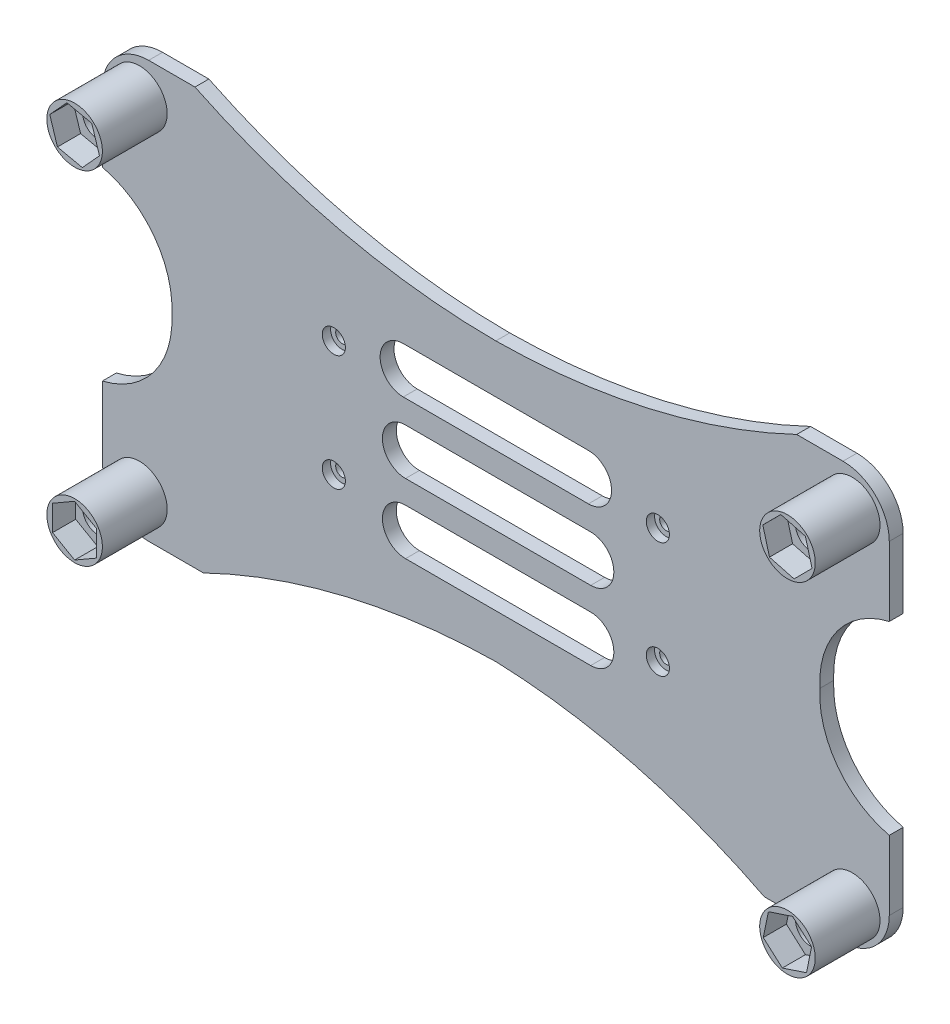
SolidWorks part; units mm, degrees
ref_plane "前视基准面" through (0, 0, 0) normal (0, 0, 1) x (1, 0, 0)
ref_plane "上视基准面" through (0, 0, 0) normal (0, 1, 0) x (1, 0, 0)
ref_plane "右视基准面" through (0, 0, 0) normal (1, 0, 0) x (0, 0, -1)
sketch "草图1" plane through (0, 0, 0) normal (0, 0, 1) x (1, 0, 0)
  line L1 (-72.5741, 45.4874) -> (77.4259, 45.4874)
  line L2 (-82.5741, 35.4874) -> (-82.5741, -34.5126)
  line L3 (-72.5741, -44.5126) -> (77.4259, -44.5126)
  line L4 (87.4259, 35.4874) -> (87.4259, -34.5126)
  arc A0 (-72.5741, 45.4874) -> (-82.5741, 35.4874) centre (-72.5741, 35.4874) ccw
  arc A1 (-72.5741, -44.5126) -> (-82.5741, -34.5126) centre (-72.5741, -34.5126) cw
  arc A2 (87.4259, 35.4874) -> (77.4259, 45.4874) centre (77.4259, 35.4874) ccw
  arc A3 (87.4259, -34.5126) -> (77.4259, -44.5126) centre (77.4259, -34.5126) cw
  dimension "D1" = 10
  dimension "D2" = 10
  dimension "D3" = 10
  dimension "D4" = 10
  dimension "D5" = 90
  dimension "D6" = 170
extrude "凸台-拉伸1" add sketch "草图1" along normal blind 3
ref_plane "for screw hole" through (0, 0, 3) normal (0, 0, 1) x (1, 0, 0)
sketch "草图2" plane through (0, 0, 3) normal (0, 0, 1) x (1, 0, 0)
  line L0 (77.4259, 45.4874) -> (-72.5741, 45.4874) construction
  line L1 (-82.5741, 35.4874) -> (-82.5741, -34.5126) construction
  line L2 (-72.5741, -44.5126) -> (77.4259, -44.5126) construction
  line L3 (87.4259, -34.5126) -> (87.4259, 35.4874) construction
  line L4 (-60.7497, -44.5126) -> (60.4378, -44.5126)
  line L5 (-62.5741, 45.4874) -> (67.4259, 45.4874)
  line L6 (87.4259, 20.4874) -> (87.4259, -19.5126)
  line L7 (-82.5741, 20.4874) -> (-82.5741, -19.5126)
  line L8 (-17.5741, 15) -> (22.4259, 15) construction
  line L9 (-17.5741, 20) -> (22.4259, 20)
  line L10 (-17.5741, 10) -> (22.4259, 10)
  line L11 (-17.0794, 0) -> (22.9206, 0) construction
  line L12 (-17.0794, 5) -> (22.9206, 5)
  line L13 (-17.0794, -5) -> (22.9206, -5)
  line L14 (-17.0794, -15) -> (22.9206, -15) construction
  line L15 (-17.0794, -10) -> (22.9206, -10)
  line L16 (-17.0794, -20) -> (22.9206, -20)
  circle A0 centre (-32.5741, 12.9874) radius 1.4
  circle A1 centre (-32.5741, -12.0126) radius 1.4
  circle A2 centre (37.4259, 12.9874) radius 1.4
  circle A3 centre (37.4259, -12.0126) radius 1.4
  arc A4 (67.4259, 45.4874) -> (2.4259, 30.4874) centre (1.0956, 184.5854) cw
  arc A5 (-62.5741, 45.4874) -> (2.4259, 30.4874) centre (2.8104, 180.4869) ccw
  arc A6 (-60.7497, -44.5126) -> (2.4259, -29.5126) centre (4.6684, -179.4958) cw
  arc A7 (60.4378, -44.5126) -> (2.4259, -29.5126) centre (-2.3985, -167.85) ccw
  arc A8 (87.4259, 20.4874) -> (72.4259, 0.4874) centre (91.8434, 1.5492) ccw
  arc A9 (87.4259, -19.5126) -> (72.4259, 0.4874) centre (91.8434, -0.5745) cw
  arc A10 (-82.5741, 20.4874) -> (-67.5741, 0.4874) centre (-86.9917, 1.5492) cw
  arc A11 (-82.5741, -19.5126) -> (-67.5741, 0.4874) centre (-86.9917, -0.5745) ccw
  arc A12 (-17.5741, 20) -> (-17.5741, 10) centre (-17.5741, 15) ccw
  arc A13 (22.4259, 10) -> (22.4259, 20) centre (22.4259, 15) ccw
  arc A14 (-17.0794, 5) -> (-17.0794, -5) centre (-17.0794, 0) ccw
  arc A15 (22.9206, -5) -> (22.9206, 5) centre (22.9206, 0) ccw
  arc A16 (-17.0794, -10) -> (-17.0794, -20) centre (-17.0794, -15) ccw
  arc A17 (22.9206, -20) -> (22.9206, -10) centre (22.9206, -15) ccw
  point P12 (2.4259, 30.4874)
  point P13 (2.4259, -29.5126)
  point P16 (-62.5741, 45.4874)
  point P17 (67.4259, 45.4874)
  point P18 (-60.7497, -44.5126)
  point P19 (60.4378, -44.5126)
  point P29 (-67.5741, 0.4874)
  point P33 (72.4259, 0.4874)
  point P34 (-82.5741, 20.4874)
  point P35 (-82.5741, -19.5126)
  point P36 (87.4259, -19.5126)
  point P37 (87.4259, 20.4874)
  point P54 (2.4259, 15)
  point P61 (2.9206, 0)
  point P68 (2.9206, -15)
  dimension "D2" = 2.8
  dimension "D3" = 2.8
  dimension "D4" = 2.8
  dimension "D8" = 32.5
  dimension "D9" = 50
  dimension "D10" = 50
  dimension "D11" = 2.8
  dimension "D21" = 45
  dimension "D29" = 15
  dimension "D5" = 70
  dimension "D6" = 70
  dimension "D7" = 25
  dimension "D12" = 25
  dimension "D13" = 32.5
  dimension "D14" = 85
  dimension "D15" = 15
  dimension "D16" = 85
  dimension "D17" = 15
  dimension "D18" = 20
  dimension "D19" = 20
  dimension "D20" = 26.9881
  dimension "D22" = 15
  dimension "D23" = 15
  dimension "D24" = 45
  dimension "D25" = 25
  dimension "D26" = 25
  dimension "D27" = 25
  dimension "D28" = 25
  dimension "D30" = 15
  dimension "D31" = 15
extrude "切除-拉伸1" cut sketch "草图2" against normal blind 10 and the other way blind 42
ref_plane "for outer screw hole" through (0, 0, 3) normal (0, 0, 1) x (1, 0, 0)
sketch "草图3" plane through (0, 0, 3) normal (0, 0, 1) x (1, 0, 0)
  circle A0 centre (-32.5741, 12.9874) radius 2.5
  circle A1 centre (37.4259, 12.9874) radius 2.5
  circle A2 centre (37.4259, -12.0126) radius 2.5
  circle A3 centre (-32.5741, -12.0126) radius 2.5
  dimension "D1" = 5
  dimension "D2" = 5
  dimension "D3" = 5
  dimension "D4" = 5
extrude "切除-拉伸2" cut sketch "草图3" against normal blind 1.8
ref_plane "for stands" through (0, 0, 3) normal (0, 0, 1) x (1, 0, 0)
sketch "草图7" plane through (0, 0, 3) normal (0, 0, 1) x (1, 0, 0)
  line L0 (77.4259, 45.4874) -> (67.4259, 45.4874) construction
  line L1 (-82.5741, 35.4874) -> (-82.5741, 20.4874) construction
  line L2 (-72.5741, -44.5126) -> (-60.7497, -44.5126) construction
  line L3 (87.4259, -34.5126) -> (87.4259, -19.5126) construction
  circle A0 centre (-74.5741, 37.4874) radius 6
  circle A1 centre (-74.5741, -36.5126) radius 6
  circle A2 centre (79.4259, 37.4874) radius 6
  circle A3 centre (79.4259, -36.5126) radius 6
  point P12 (79.4259, -30.5126)
  point P14 (79.4259, 31.4874)
  dimension "D1" = 12
  dimension "D2" = 12
  dimension "D3" = 12
  dimension "D4" = 12
  dimension "D7" = 8
  dimension "D5" = 8
  dimension "D6" = 8
  dimension "D8" = 8
  dimension "D9" = 8
  dimension "D10" = 8
  dimension "D11" = 8
  dimension "D12" = 8
extrude "凸台-拉伸4" add sketch "草图7" along normal blind 14
ref_plane "button left hole" through (0, 0, 17) normal (0, 0, 1) x (1, 0, 0)
ref_plane "up left hole" through (0, 0, 17) normal (0, 0, 1) x (1, 0, 0)
ref_plane "up right hole" through (0, 0, 17) normal (0, 0, 1) x (1, 0, 0)
ref_plane "button right hole" through (0, 0, 17) normal (0, 0, 1) x (1, 0, 0)
sketch "草图9" plane through (0, 0, 17) normal (0, 0, 1) x (1, 0, 0)
  line L1 (-69.811, -39.2626) -> (-69.811, -33.7626)
  line L2 (-69.811, -33.7626) -> (-74.5741, -31.0126)
  line L3 (-74.5741, -31.0126) -> (-79.3373, -33.7626)
  line L4 (-79.3373, -33.7626) -> (-79.3373, -39.2626)
  line L5 (-79.3373, -39.2626) -> (-74.5741, -42.0126)
  line L6 (-74.5741, -42.0126) -> (-69.811, -39.2626)
  circle A0 centre (-74.5741, -36.5126) radius 4.7631 construction
  circle A1 centre (-74.5741, -36.5126) radius 6 construction
  dimension "D1" = 5.5
  dimension "D2" = 0
extrude "button left nut " cut sketch "草图9" against normal blind 5
sketch "草图10" plane through (0, 0, 17) normal (0, 0, 1) x (1, 0, 0)
  line L1 (-72.9093, 32.2454) -> (-69.202, 36.3081)
  line L2 (-69.202, 36.3081) -> (-70.8668, 41.5501)
  line L3 (-70.8668, 41.5501) -> (-76.2389, 42.7294)
  line L4 (-76.2389, 42.7294) -> (-79.9462, 38.6666)
  line L5 (-79.9462, 38.6666) -> (-78.2814, 33.4246)
  line L6 (-78.2814, 33.4246) -> (-72.9093, 32.2454)
  circle A0 centre (-74.5741, 37.4874) radius 4.7631 construction
  circle A1 centre (-74.5741, 37.4874) radius 6 construction
  dimension "D1" = 5.5
  dimension "D2" = 0
extrude "up left nut" cut sketch "草图10" against normal blind 5
sketch "草图11" plane through (0, 0, 17) normal (0, 0, 1) x (1, 0, 0)
  line L1 (80.8593, 32.1775) -> (84.7411, 36.0738)
  line L2 (84.7411, 36.0738) -> (83.3077, 41.3838)
  line L3 (83.3077, 41.3838) -> (77.9924, 42.7973)
  line L4 (77.9924, 42.7973) -> (74.1106, 38.9009)
  line L5 (74.1106, 38.9009) -> (75.5441, 33.591)
  line L6 (75.5441, 33.591) -> (80.8593, 32.1775)
  circle A0 centre (79.4259, 37.4874) radius 4.7631 construction
  circle A2 centre (79.4259, 37.4874) radius 6 construction
  dimension "D2" = 0
  dimension "D1" = 5.5
extrude "up right nut" cut sketch "草图11" against normal blind 5
sketch "草图12" plane through (0, 0, 17) normal (0, 0, 1) x (1, 0, 0)
  line L1 (83.5366, -40.1666) -> (84.6457, -34.7796)
  line L2 (84.6457, -34.7796) -> (80.535, -31.1256)
  line L3 (80.535, -31.1256) -> (75.3151, -32.8586)
  line L4 (75.3151, -32.8586) -> (74.2061, -38.2456)
  line L5 (74.2061, -38.2456) -> (78.3168, -41.8996)
  line L6 (78.3168, -41.8996) -> (83.5366, -40.1666)
  circle A0 centre (79.4259, -36.5126) radius 4.7631 construction
  circle A1 centre (79.4259, -36.5126) radius 6 construction
  dimension "D2" = 0
  dimension "D1" = 5.5
extrude "button right nut" cut sketch "草图12" against normal blind 5
ref_plane "基准面13" through (0, 0, 17) normal (0, 0, 1) x (1, 0, 0)
ref_plane "基准面14" through (0, 0, 17) normal (0, 0, 1) x (1, 0, 0)
ref_plane "基准面15" through (0, 0, 17) normal (0, 0, 1) x (1, 0, 0)
ref_plane "基准面16" through (0, 0, 17) normal (0, 0, 1) x (1, 0, 0)
sketch "草图13" plane through (0, 0, 17) normal (0, 0, 1) x (1, 0, 0)
  circle A0 centre (-74.5741, -36.5126) radius 3.25
  dimension "D1" = 6.5
extrude "切除-拉伸7" cut sketch "草图13" against normal blind 13
sketch "草图15" plane through (0, 0, 17) normal (0, 0, 1) x (1, 0, 0)
  circle A0 centre (-74.5741, 37.4874) radius 3.25
  circle A1 centre (-74.5741, 37.4874) radius 6 construction
  dimension "D1" = 6.5
  dimension "D2" = 0
extrude "切除-拉伸8" cut sketch "草图15" against normal blind 13
sketch "草图16" plane through (0, 0, 17) normal (0, 0, 1) x (1, 0, 0)
  circle A0 centre (79.4259, 37.4874) radius 3.25
  dimension "D1" = 6.5
extrude "切除-拉伸9" cut sketch "草图16" against normal blind 13
sketch "草图17" plane through (0, 0, 17) normal (0, 0, 1) x (1, 0, 0)
  circle A0 centre (79.4259, -36.5126) radius 3.25
  circle A1 centre (79.4259, -36.5126) radius 6 construction
  point P4 (79.4259, -36.2982)
  point P5 (79.4259, -36.2982)
  point P6 (79.4259, -36.2982)
  point P7 (79.4259, -36.2982)
  dimension "D1" = 6.5
  dimension "D2" = 0
extrude "切除-拉伸10" cut sketch "草图17" against normal blind 13
